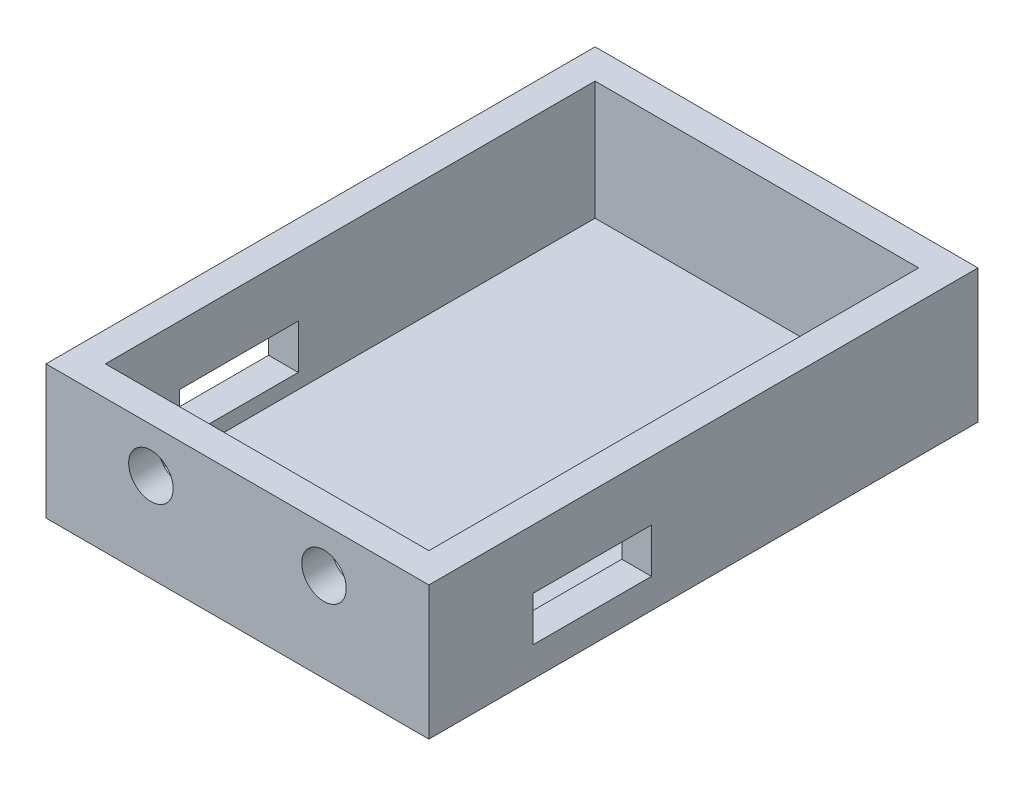
SolidWorks part; units mm, degrees
ref_plane "Front Plane" through (0, 0, 0) normal (0, 0, 1) x (1, 0, 0)
ref_plane "Top Plane" through (0, 0, 0) normal (0, 1, 0) x (1, 0, 0)
ref_plane "Right Plane" through (0, 0, 0) normal (1, 0, 0) x (0, 0, -1)
sketch "Sketch1" plane through (0, 0, 0) normal (0, 1, 0) x (1, 0, 0)
  line L0 (12.9, -18.5) -> (12.9, 18.5)
  line L1 (-10.9, -16.5) -> (10.9, -16.5)
  line L2 (-10.9, -16.5) -> (-10.9, 16.5)
  line L3 (-10.9, 16.5) -> (10.9, 16.5)
  line L4 (10.9, -16.5) -> (10.9, 16.5)
  line L5 (-10.9, -16.5) -> (10.9, 16.5) construction
  line L6 (-10.9, 16.5) -> (10.9, -16.5) construction
  line L7 (-12.9, 18.5) -> (12.9, 18.5)
  line L8 (-12.9, -18.5) -> (-12.9, 18.5)
  line L9 (-12.9, -18.5) -> (12.9, -18.5)
  point P0 (0, 0)
  dimension "D1" = 21.8
  dimension "D2" = 33
  dimension "D3" = 2
extrude "Boss-Extrude2" add sketch "Sketch1" along normal blind 1
sketch "Sketch3" plane through (0, 1, 0) normal (0, 1, 0) x (1, 0, 0)
  line L0 (-10.9, 16.5) -> (-10.9, -16.5) construction
  line L1 (10.9, 16.5) -> (-10.9, 16.5) construction
  line L2 (10.9, -16.5) -> (10.9, 16.5) construction
  line L3 (-10.9, -16.5) -> (10.9, -16.5) construction
  line L4 (-12.9, -18.5) -> (12.9, -18.5)
  line L5 (12.9, -18.5) -> (12.9, 18.5)
  line L6 (12.9, 18.5) -> (-12.9, 18.5)
  line L7 (-12.9, 18.5) -> (-12.9, -18.5)
  line L8 (-12.9, -18.5) -> (12.9, -18.5)
  line L9 (12.9, -18.5) -> (12.9, -11.5)
  line L10 (12.9, 18.5) -> (-12.9, 18.5)
  line L11 (-12.9, 18.5) -> (-12.9, -3.5)
  line L12 (-10.9, 16.5) -> (-10.9, -3.5)
  line L13 (10.9, 16.5) -> (-10.9, 16.5)
  line L14 (10.9, -16.5) -> (10.9, -11.5)
  line L15 (-10.9, -16.5) -> (10.9, -16.5)
  line L16 (0, 18.5) -> (0, -18.5) construction
  line L17 (-10.9, -11.5) -> (-12.9, -11.5)
  line L18 (-10.9, -11.5) -> (-10.9, -3.5)
  line L19 (-10.9, -3.5) -> (-12.9, -3.5)
  line L20 (-10.9, -11.5) -> (-10.9, -16.5)
  line L21 (10.9, -11.5) -> (12.9, -11.5)
  line L22 (10.9, -3.5) -> (12.9, -3.5)
  line L23 (-12.9, -11.5) -> (-12.9, -18.5)
  line L24 (10.9, -3.5) -> (10.9, 16.5)
  line L25 (12.9, -3.5) -> (12.9, 18.5)
  line M11 (-12.9, 18.5) -> (-12.9, -18.5)
  line M12 (-10.9, 16.5) -> (10.9, 16.5)
  line M15 (-10.9, -16.5) -> (-10.9, 16.5)
  dimension "D2" = 8
  dimension "D3" = 7
  dimension "D1" = 0
extrude "Boss-Extrude3" add sketch "Sketch3" along normal blind 3 contours L16 L10 L19 M11 M15 M12 | L20 L15 L14 L21 L9 L8 L23 L17
sketch "Sketch4" plane through (0, 0, 0) normal (0, -1, 0) x (1, 0, 0)
  line L4 (12.9, 18.5) -> (-12.9, 18.5)
  line L5 (-12.9, 18.5) -> (-12.9, -18.5)
  line L6 (-12.9, -18.5) -> (12.9, -18.5)
  line L7 (12.9, -18.5) -> (12.9, 18.5)
  line L8 (12.9, 18.5) -> (-12.9, 18.5)
  line L9 (-12.9, 18.5) -> (-12.9, -18.5)
  line L10 (-12.9, -18.5) -> (12.9, -18.5)
  line L11 (12.9, -18.5) -> (12.9, 18.5)
  dimension "D1" = 0
extrude "Boss-Extrude4" add sketch "Sketch4" along normal blind 1
sketch "Sketch5" plane through (0, 4, 0) normal (0, 1, 0) x (1, 0, 0)
  line L1 (-12.9, -18.5) -> (12.9, -18.5)
  line L2 (-12.9, -18.5) -> (-12.9, 18.5)
  line L3 (-12.9, 18.5) -> (12.9, 18.5)
  line L4 (12.9, -18.5) -> (12.9, 18.5)
  line L5 (-10.9, -16.5) -> (10.9, -16.5)
  line L6 (-10.9, -16.5) -> (-10.9, 16.5)
  line L7 (-10.9, 16.5) -> (10.9, 16.5)
  line L8 (10.9, -16.5) -> (10.9, 16.5)
extrude "Boss-Extrude5" add sketch "Sketch5" along normal blind 4
sketch "Sketch6" plane through (0, 0, 18.5) normal (0, 0, 1) x (1, 0, 0)
  line L0 (0, 8) -> (0, -1) construction
  line L1 (-12.9, 8) -> (12.9, 8) construction
  line L2 (12.9, -1) -> (-12.9, -1) construction
  circle A0 centre (-5.8309, 5) radius 1.5
  circle A1 centre (5.8309, 5) radius 1.5
  dimension "D1" = 3
  dimension "D2" = 3
extrude "Cut-Extrude1" cut sketch "Sketch6" against normal blind 4
